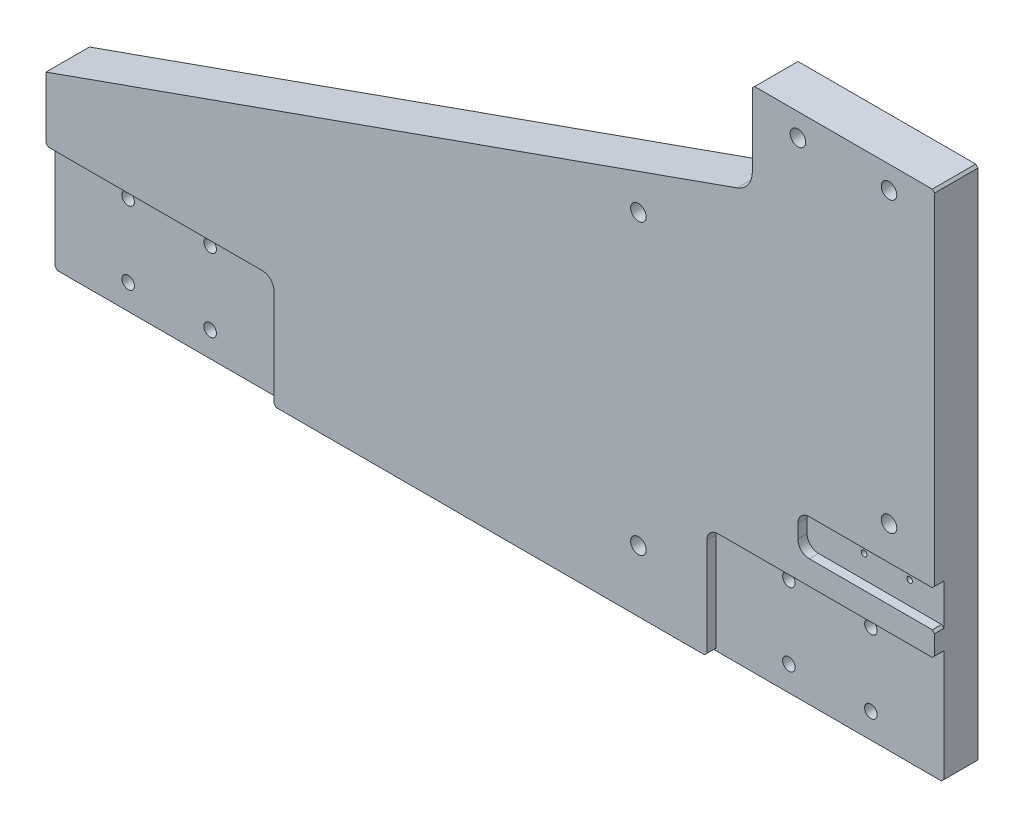
SolidWorks part; units mm, degrees
material "6061-T6 (SS)"
ref_plane "Front Plane" through (0, 0, 0) normal (0, 0, 1) x (1, 0, 0)
ref_plane "Top Plane" through (0, 0, 0) normal (0, 1, 0) x (1, 0, 0)
ref_plane "Right Plane" through (0, 0, 0) normal (1, 0, 0) x (0, 0, -1)
sketch "Sketch1" plane through (0, 0, 0) normal (0, 0, 1) x (1, 0, 0)
  line L0 (-195, 50) -> (-195, -27)
  line L1 (195, -27) -> (195, 200)
  line L2 (195, 200) -> (115, 200)
  line L3 (145, 0) -> (-145, 0) construction
  line L4 (-163, -16) -> (-127, -16) construction
  line L5 (-163, -16) -> (-163, 16) construction
  line L6 (-163, 16) -> (-127, 16) construction
  line L7 (-127, -16) -> (-127, 16) construction
  line L8 (-163, -16) -> (-127, 16) construction
  line L9 (-163, 16) -> (-127, -16) construction
  line L10 (127, -16) -> (163, -16) construction
  line L11 (127, -16) -> (127, 16) construction
  line L12 (127, 16) -> (163, 16) construction
  line L13 (163, -16) -> (163, 16) construction
  line L14 (127, -16) -> (163, 16) construction
  line L15 (127, 16) -> (163, -16) construction
  line L16 (115, 160) -> (115, 200)
  line L17 (195, -27) -> (-195, -27)
  line L18 (115, 160) -> (-195, 50)
  line L19 (-106.25, 22) -> (-183.75, 22) construction
  line L20 (-106.25, 22) -> (-106.25, -22) construction
  line L21 (-106.25, -22) -> (-183.75, -22) construction
  line L22 (-183.75, 22) -> (-183.75, -22) construction
  line L23 (-106.25, 22) -> (-183.75, -22) construction
  line L24 (-106.25, -22) -> (-183.75, 22) construction
  line L25 (42.6, 207.0034) -> (42.6, 177.935) construction
  point P6 (-145, 0)
  point P11 (145, 0)
  dimension "D1" = 36
  dimension "D2" = 32
  dimension "D3" = 290
  dimension "D4" = 50
  dimension "D5" = 200
  dimension "D6" = 77.5
  dimension "D7" = 50
  dimension "D8" = 44
  dimension "D9" = 27
  dimension "D10" = 50
  dimension "D11" = 80
  dimension "D12" = 40
  dimension "D13" = 152.4
extrude "Boss-Extrude1" add sketch "Sketch1" along normal blind 19.05
sketch "Sketch2" plane through (0, 0, 0) normal (0, 0, -1) x (-1, 0, 0)
  line L0 (195, 50) -> (195, -27) construction
  line L1 (-195, -27) -> (-95, -27)
  line L2 (-195, -27) -> (-195, 22)
  line L3 (-195, 22) -> (-100, 22)
  line L4 (195, -27) -> (195, 22)
  line L5 (106.25, 22) -> (183.75, 22) construction
  line L6 (-195, -27) -> (-195, 200) construction
  line L7 (-195, 48.5) -> (-140, 48.5)
  line L8 (-195, 48.5) -> (-195, 32.5)
  line L9 (-195, 32.5) -> (-140, 32.5)
  line L10 (-135, 43.5) -> (-135, 37.5)
  line L11 (-95, 17) -> (-95, -27)
  line L12 (95, 17) -> (95, -27)
  line L13 (100, 22) -> (195, 22)
  line L14 (95, -27) -> (195, -27)
  arc A0 (-140, 32.5) -> (-135, 37.5) centre (-140, 37.5) ccw
  arc A1 (-140, 48.5) -> (-135, 43.5) centre (-140, 43.5) cw
  arc A2 (95, 17) -> (100, 22) centre (100, 17) cw
  arc A3 (-95, 17) -> (-100, 22) centre (-100, 17) ccw
  point P25 (95, 22)
  dimension "D3" = 5
  dimension "D6" = 5
  dimension "D1" = 10.5
  dimension "D2" = 16
  dimension "D4" = 60
  dimension "D5" = 100
extrude "Cut-Extrude2" cut sketch "Sketch2" against normal offset from surface (4.05 mm away) 15 up to face at (38.3333, 92.6667, 19.05)
hole_wizard "M5 Clearance Hole1" positions "Sketch5" profile "Sketch6" hole size "M5" standard "ANSI Metric" end condition up to next
sketch "Sketch5" plane through (0, 0, 4.05) normal (0, 0, -1) x (-1, 0, 0)
  point P12 (127, 16)
  point P15 (163, 16)
  point P18 (163, -16)
  point P21 (127, -16)
sketch "Sketch6" plane through (-127, 16, 4.05) normal (1, 0, 0) x (0, 1, 0)
  line L0 (0, 0) -> (0, 15)
  line L1 (0, 15) -> (2.75, 15)
  line L2 (2.75, 15) -> (2.75, 0)
  line L5 (2.75, 0) -> (0, 0)
  line L11 (0, -6.35) -> (0, 107.95) construction
  dimension "Thru Hole Dia." = 5.5
  dimension "Thru Hole Depth" = 15
hole_wizard "M5 Clearance Hole2" positions "Sketch11" profile "Sketch12" hole size "M5" standard "ANSI Metric" end condition through all
sketch "Sketch11" plane through (0, 0, 4.05) normal (0, 0, -1) x (-1, 0, 0)
  point P0 (-163, 16)
  point P3 (-127, 16)
  point P6 (-127, -16)
  point P9 (-163, -16)
sketch "Sketch12" plane through (163, 16, 4.05) normal (1, 0, 0) x (0, 1, 0)
  line L0 (0, 0) -> (0, 15)
  line L1 (0, 15) -> (2.75, 15)
  line L2 (2.75, 15) -> (2.75, 0)
  line L5 (2.75, 0) -> (0, 0)
  line L11 (0, -6.35) -> (0, 107.95) construction
  dimension "Thru Hole Dia." = 5.5
  dimension "Thru Hole Depth" = 15
hole_wizard "M3x0.5 Tapped Hole1" positions "Sketch3" profile "Sketch4" tap size "M3x0.5" standard "ANSI Metric"
sketch "Sketch3" plane through (0, 0, 4.05) normal (0, 0, -1) x (-1, 0, 0)
  line L0 (-180, 42.5) -> (-160, 42.5)
  line L3 (-195, 32.5) -> (-140, 32.5) construction
  line L4 (-195, -27) -> (-195, 200) construction
  point P1 (-180, 42.5)
  point P2 (-160, 42.5)
  point P8 (-170, 42.5)
  dimension "D1" = 10
  dimension "D2" = 20
  dimension "D3" = 25
sketch "Sketch4" plane through (180, 42.5, 4.05) normal (1, 0, 0) x (0, 1, 0)
  line L0 (0, 0) -> (0, 8.2511)
  line L1 (0, 8.2511) -> (1.25, 7.5)
  line L2 (1.25, 7.5) -> (1.25, 0)
  line L5 (1.25, 0) -> (0, 0)
  line L10 (0, 8.2511) -> (-1.25, 7.5) construction
  line L11 (0, -6.35) -> (0, 107.95) construction
  dimension "Tap Drill Dia." = 2.5
  dimension "Tap Drill Depth" = 7.5
  dimension "Drill Angle" = 118
cosmetic thread "Hole Thread3" parameters "D1"=6, "D2"=3
cosmetic thread "Hole Thread4" parameters "D1"=6, "D2"=3
hole_wizard "M8x1.25 Tapped Hole1" positions "Sketch7" profile "Sketch8" tap size "M8x1.25" standard "ANSI Metric" end condition up to next
sketch "Sketch7" plane through (0, 0, 0) normal (0, 0, -1) x (-1, 0, 0)
  line L0 (-175, 190) -> (-135, 190)
  line L1 (-175, 190) -> (-175, 126.6667)
  line L2 (-175, 126.6667) -> (-175, 63.3333)
  line L3 (-175, 63.3333) -> (-175, 0)
  line L4 (-175, 0) -> (-65, 0)
  line L5 (-145, 0) -> (145, 0) construction
  line L6 (-65, 0) -> (-65, 126.6667)
  line L7 (-65, 126.6667) -> (-175, 126.6667)
  line L8 (-155, 190) -> (-155, 200)
  line L9 (-195, 200) -> (-115, 200) construction
  line L11 (-175, 95) -> (-195, 95)
  line L12 (-195, -27) -> (-195, 200) construction
  point P1 (-175, 190)
  point P2 (-135, 190)
  point P49 (-65, 126.6667)
  point P52 (-175, 63.3333)
  point P55 (-65, 0)
  dimension "D1" = 40
  dimension "D2" = 10
  dimension "D3" = 110
sketch "Sketch8" plane through (175, 190, 0) normal (1, 0, 0) x (0, 1, 0)
  line L0 (0, 0) -> (0, 19.05)
  line L1 (0, 19.05) -> (3.4, 19.05)
  line L2 (3.4, 19.05) -> (3.4, 0)
  line L5 (3.4, 0) -> (0, 0)
  line L11 (0, -6.35) -> (0, 107.95) construction
  dimension "Thru Tap Drill Dia." = 6.8
  dimension "Thru Tap Drill Depth" = 19.05
cosmetic thread "Hole Thread7" parameters "D2"=8
cosmetic thread "Hole Thread19" parameters "D2"=8
cosmetic thread "Hole Thread20" parameters "D2"=8
cosmetic thread "Hole Thread21" parameters "D2"=8
cosmetic thread "Hole Thread22" parameters "D2"=8
hole_wizard "M8 Clearance Hole1" [suppressed] positions "Sketch9" profile "Sketch10" hole size "M8" standard "ANSI Metric"
sketch "Sketch9" plane through (0, 0, 0) normal (0, 0, -1) x (-1, 0, 0)
  line L0 (17.4, 80) -> (-22.6, 80)
  line L2 (-145, 0) -> (145, 0) construction
  line L3 (-42.6, 200207.0034) -> (-42.6, -199822.065) construction
  point P0 (-22.6, 80)
  point P2 (17.4, 80)
  dimension "D1" = 40
  dimension "D2" = 80
  dimension "D3" = 20
sketch "Sketch10" plane through (22.6, 80, 0) normal (1, 0, 0) x (0, 1, 0)
  line L0 (0, 0) -> (0, 19.05)
  line L1 (0, 19.05) -> (4.5, 19.05)
  line L2 (4.5, 19.05) -> (4.5, 0)
  line L5 (4.5, 0) -> (0, 0)
  line L11 (0, -6.35) -> (0, 107.95) construction
  dimension "Thru Hole Dia." = 9
  dimension "Thru Hole Depth" = 19.05
hole_wizard "M3x0.5 Tapped Hole2" [suppressed] positions "Sketch13" profile "Sketch14" tap size "M3x0.5" standard "ANSI Metric"
sketch "Sketch13" plane through (0, 0, 0) normal (0, 0, -1) x (-1, 0, 0)
  line L0 (-3.6, -22) -> (8.4, -22)
  line L3 (-88.6, -22) -> (-76.6, -22)
  line L5 (10.4775, 0) -> (-10.4775, 0) construction
  line L6 (-42.6, 200207.0034) -> (-42.6, -199822.065) construction
  point P1 (-3.6, -22)
  point P2 (8.4, -22)
  point P7 (-76.6, -22)
  point P9 (2.4, -22)
  point P24 (-88.6, -22)
  point P27 (-82.6, -22)
  dimension "D1" = 12
  dimension "D2" = 40
  dimension "D3" = 22
  dimension "D4" = 45
sketch "Sketch14" plane through (3.6, -22, 0) normal (1, 0, 0) x (0, 1, 0)
  line L0 (0, 0) -> (0, 8.2511)
  line L1 (0, 8.2511) -> (1.25, 7.5)
  line L2 (1.25, 7.5) -> (1.25, 0)
  line L5 (1.25, 0) -> (0, 0)
  line L10 (0, 8.2511) -> (-1.25, 7.5) construction
  line L11 (0, -6.35) -> (0, 107.95) construction
  dimension "Tap Drill Dia." = 2.5
  dimension "Tap Drill Depth" = 7.5
  dimension "Drill Angle" = 118
cosmetic thread "Hole Thread23" [suppressed] parameters "D1"=6, "D2"=3
cosmetic thread "Hole Thread24" [suppressed] parameters "D1"=6, "D2"=3
cosmetic thread "Hole Thread25" [suppressed] parameters "D1"=6, "D2"=3
cosmetic thread "Hole Thread26" [suppressed] parameters "D1"=6, "D2"=3
fillet "Fillet1" radius 10 1 edges at (115, 160, 9.525)
chamfer "Chamfer1" distance 1 10 edges at (-195, -27, 11.55) (195, -27, 11.55) (115, 200, 9.525) (195, 200, 9.525) (195, 22, 2.025) (195, 32.5, 2.025) (195, 48.5, 2.025) (-95, -27, 2.025) (95, -27, 2.025) (-195, 22, 2.025)
mirror "Mirror1" about plane through (0, 0, 0) normal (0, 0, 1) of bodies 105
cosmetic thread "Hole Thread27" parameters "D1"=6, "D2"=3
cosmetic thread "Hole Thread28" parameters "D2"=8
cosmetic thread "Hole Thread29" parameters "D2"=8
cosmetic thread "Hole Thread30" parameters "D2"=8
cosmetic thread "Hole Thread31" parameters "D2"=8
cosmetic thread "Hole Thread32" parameters "D1"=6, "D2"=3
cosmetic thread "Hole Thread33" parameters "D2"=8
delete or keep bodies "Body-Delete/Keep 1" type delete bodies bodies 105
